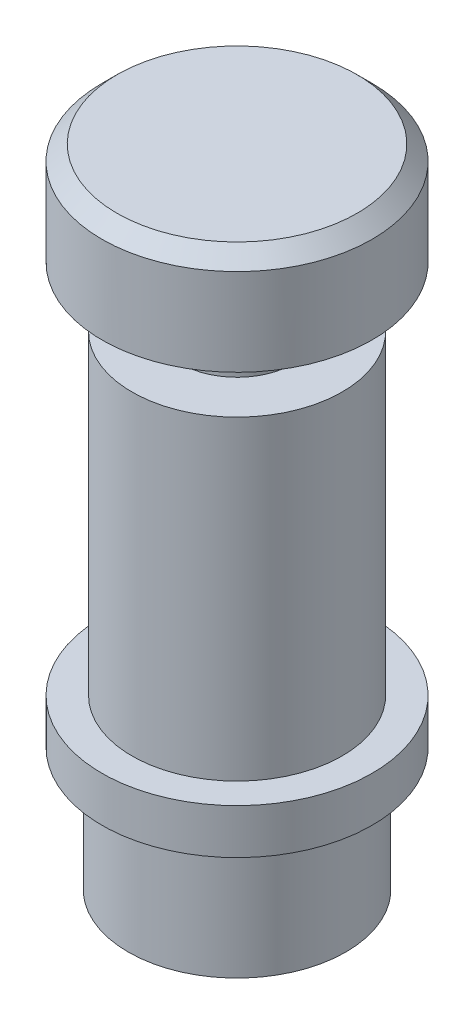
SolidWorks part; units mm, degrees
material "Plain Carbon Steel"
ref_plane "Front Plane" through (0, 0, 0) normal (0, 0, 1) x (1, 0, 0)
ref_plane "Top Plane" through (0, 0, 0) normal (0, 1, 0) x (1, 0, 0)
ref_plane "Right Plane" through (0, 0, 0) normal (1, 0, 0) x (0, 0, -1)
sketch "Sketch2" plane through (0, 0, 0) normal (0, 0, 1) x (1, 0, 0)
  line L0 (0, 0) -> (0, 50) construction
  line L1 (0, 0) -> (7.25, 0)
  line L2 (7.25, 0) -> (7.25, 8.1886)
  line L3 (7.25, 8.1886) -> (9, 8.1886)
  line L4 (9, 8.1886) -> (9, 11.1886)
  line L5 (9, 11.1886) -> (7, 11.1886)
  line L6 (7, 11.1886) -> (7, 32.1886)
  line L7 (7, 32.1886) -> (3.75, 32.1886)
  line L8 (3.75, 32.1886) -> (3.75, 36.1886)
  line L9 (3.75, 36.1886) -> (9, 36.1886)
  line L10 (9, 36.1886) -> (9, 43)
  line L11 (9, 43) -> (0, 43)
  line L12 (0, 0) -> (0, 43)
  dimension "D1" = 50
  dimension "D2" = 43
  dimension "D3" = 3
  dimension "D4" = 25
  dimension "D5" = 4
  dimension "D6" = 7.25
  dimension "D7" = 9
  dimension "D8" = 7
  dimension "D9" = 3.75
  dimension "D10" = 9
revolve "Revolve5" add sketch "Sketch2" angle 360 about L0
chamfer "Chamfer1" distance 1 angle 45 1 edges at (0, 43, -9)
